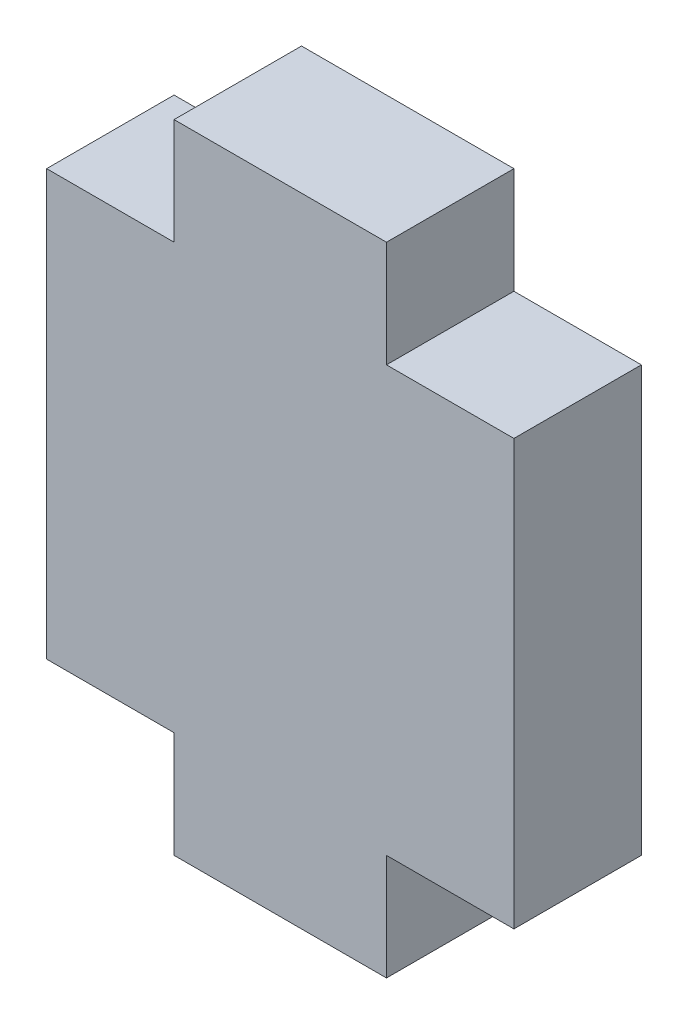
SolidWorks part; units mm, degrees
ref_plane "前视基准面" through (0, 0, 0) normal (0, 0, 1) x (1, 0, 0)
ref_plane "上视基准面" through (0, 0, 0) normal (0, 1, 0) x (1, 0, 0)
ref_plane "右视基准面" through (0, 0, 0) normal (1, 0, 0) x (0, 0, -1)
sketch "草图1" plane through (0, 0, 0) normal (0, 0, 1) x (1, 0, 0)
  line L0 (-15.4839, 0) -> (13.629, 0) construction
  line L1 (-2.5, 7.5) -> (2.5, 7.5)
  line L2 (-2.5, 7.5) -> (-2.5, -7.5)
  line L3 (-2.5, -7.5) -> (2.5, -7.5)
  line L4 (2.5, 7.5) -> (2.5, -7.5)
  line L5 (-2.5, 7.5) -> (2.5, -7.5) construction
  line L6 (-2.5, -7.5) -> (2.5, 7.5) construction
  line L7 (0, 8.629) -> (0, -10.4301) construction
  line L8 (-2.5, 5) -> (-5.5, 5)
  line L9 (-2.5, 5) -> (-2.5, -5)
  line L10 (-2.5, -5) -> (-5.5, -5)
  line L11 (-5.5, 5) -> (-5.5, -5)
  line L12 (2.5, -5) -> (5.5, -5)
  line L13 (5.5, 5) -> (5.5, -5)
  line L14 (2.5, 5) -> (5.5, 5)
  line L15 (2.5, 5) -> (2.5, -5)
  point P0 (0, 0)
  dimension "D1" = 5
  dimension "D2" = 15
  dimension "D3" = 3
  dimension "D4" = 10
extrude "凸台-拉伸1" add sketch "草图1" along normal blind 3 contours L8 L11 L10 L2 | L4 L1 L2 L3 | L14 L4 L12 L13
